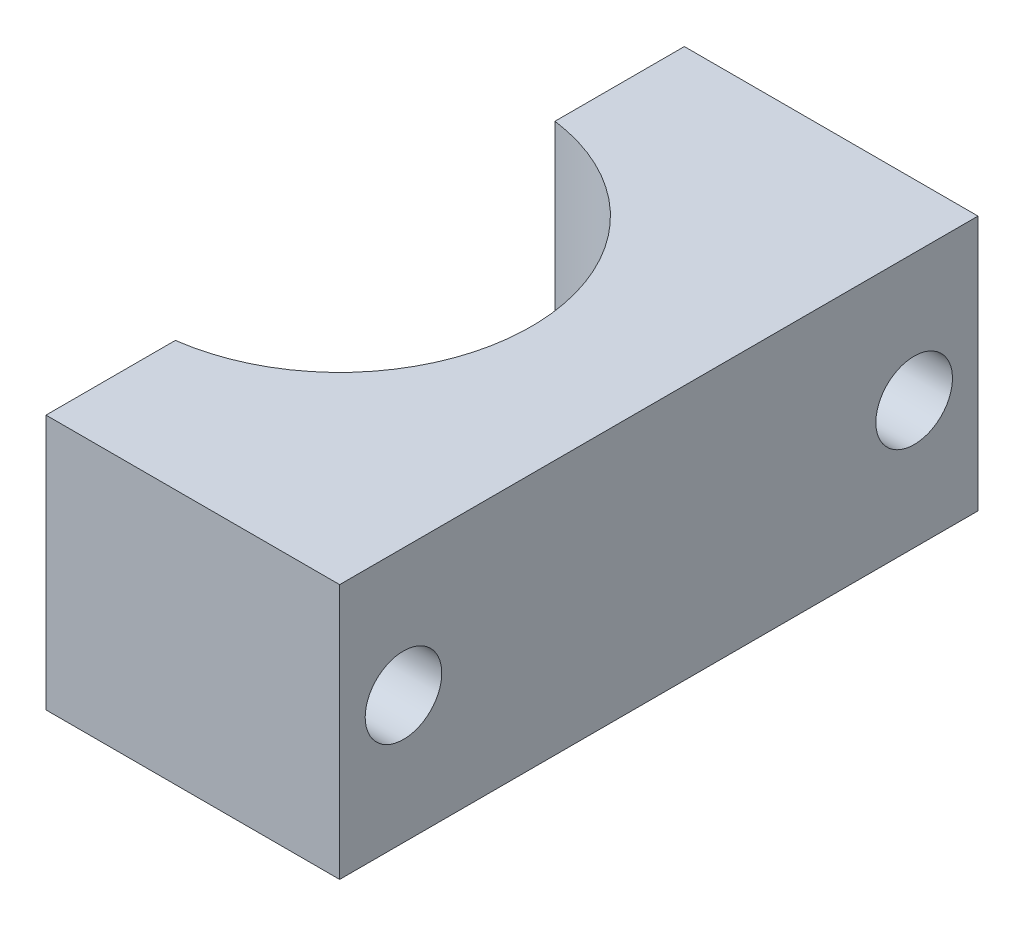
SolidWorks part; units mm, degrees
ref_plane "Front Plane" through (0, 0, 0) normal (0, 0, 1) x (1, 0, 0)
ref_plane "Top Plane" through (0, 0, 0) normal (0, 1, 0) x (1, 0, 0)
ref_plane "Right Plane" through (0, 0, 0) normal (1, 0, 0) x (0, 0, -1)
sketch "Sketch1" plane through (0, 0, 0) normal (0, 1, 0) x (1, 0, 0)
  line L0 (-12.5, -12.5) -> (12.5, -12.5)
  line L1 (-12.5, -12.5) -> (-12.5, 12.5)
  line L2 (12.5, -12.5) -> (12.5, 12.5)
  line L3 (-12.5, 12.5) -> (12.5, 12.5)
  line L4 (-12.5, -12.5) -> (12.5, 12.5) construction
  line L5 (12.5, -12.5) -> (-12.5, 12.5) construction
  point P1 (0, 0)
  dimension "D1" = 25
  dimension "D2" = 25
extrude "Boss-Extrude1" add sketch "Sketch1" along normal blind 10
sketch "Sketch2" plane through (0, 10, 0) normal (0, 1, 0) x (1, 0, 0)
  circle A1 centre (0, 0) radius 7.5
  dimension "D1" = 15
extrude "Cut-Extrude1" cut sketch "Sketch2" against normal through all
sketch "Sketch3" plane through (0, 10, 0) normal (0, 1, 0) x (1, 0, 0)
  line L0 (0, 12.5) -> (0, -12.5)
  line L1 (12.5, 12.5) -> (-12.5, 12.5) construction
  line L2 (-12.5, -12.5) -> (12.5, -12.5) construction
  line L3 (0, -12.5) -> (-12.5, -12.5)
  line L4 (-12.5, -12.5) -> (-12.5, 12.5)
  line L5 (-12.5, 12.5) -> (0, 12.5)
extrude "Cut-Extrude2" cut sketch "Sketch3" against normal blind 10
sketch "Sketch4" plane through (0, 0, 0) normal (-1, 0, 0) x (0, 0, 1)
  line L0 (-12.5, 5) -> (-7.5, 5)
  line L1 (-12.5, 0) -> (-12.5, 10) construction
  line L2 (-7.5, 10) -> (-7.5, 0) construction
  line L3 (-7.5, 5) -> (7.5, 5)
  line L4 (7.5, 0) -> (7.5, 10) construction
  line L5 (7.5, 5) -> (12.5, 5)
  line L6 (12.5, 0) -> (12.5, 10) construction
  circle A0 centre (-10, 5) radius 1.5
  circle A1 centre (10, 5) radius 1.5
extrude "Cut-Extrude3" cut sketch "Sketch4" against normal through all contours A0 | A1
sketch "Sketch5" plane through (0, 10, 0) normal (0, 1, 0) x (1, 0, 0)
  line L0 (0, 12.5) -> (1, 12.5)
  line L1 (12.5, 12.5) -> (0, 12.5) construction
  line L2 (0, 12.5) -> (0, -12.5)
  line L4 (0, -12.5) -> (1, -12.5)
  line L5 (0, -12.5) -> (0, 12.5)
  line L6 (0, 12.5) -> (1, 12.5)
  line L7 (1, -12.5) -> (1, 12.5)
  line M1 (12.5, 12.5) -> (0, 12.5)
  line M2 (0, 12.5) -> (0, 7.5)
  arc M3 (0, 7.5) -> (0, -7.5) centre (0, 0) cw
  line M4 (0, -7.5) -> (0, -12.5)
  line M5 (0, -12.5) -> (12.5, -12.5)
extrude "Cut-Extrude4" cut sketch "Sketch5" against normal through all contours L7 M3 M1 M2 | L7 M5 M3 M4 | L7 L2 M3
